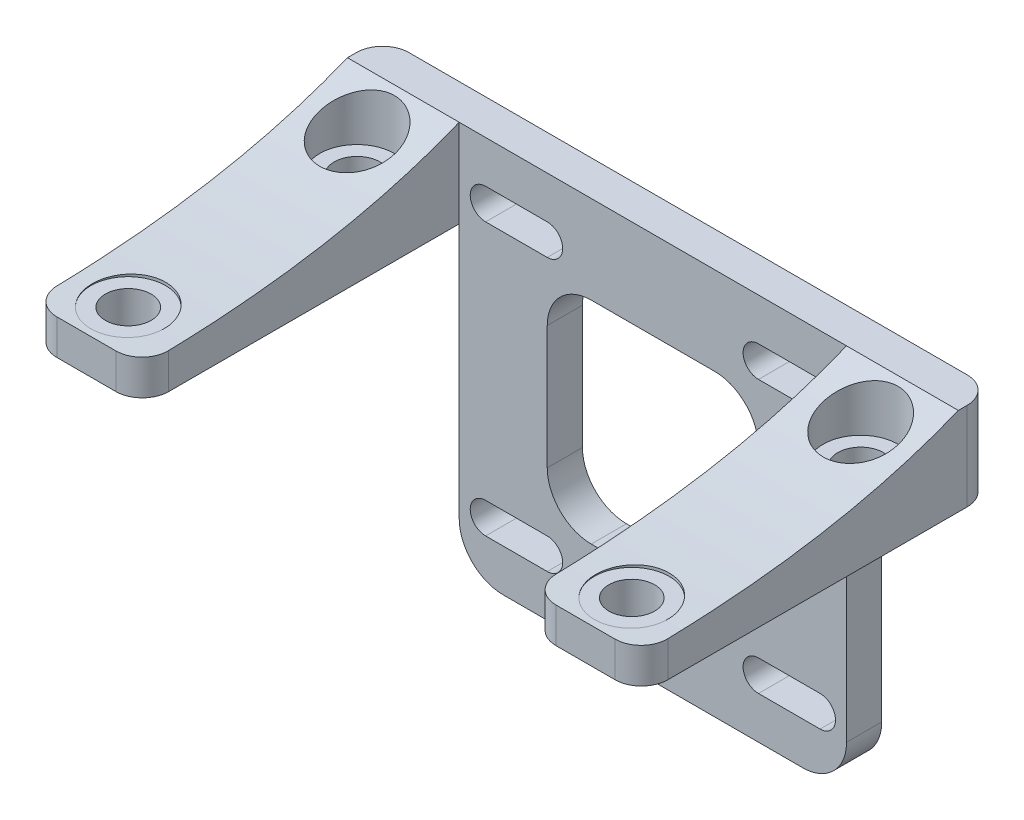
SolidWorks part; units mm, degrees
ref_plane "Front Plane" through (0, 0, 0) normal (0, 0, 1) x (1, 0, 0)
ref_plane "Top Plane" through (0, 0, 0) normal (0, 1, 0) x (1, 0, 0)
ref_plane "Right Plane" through (0, 0, 0) normal (1, 0, 0) x (0, 0, -1)
sketch "Sketch1" plane through (0, 0, 0) normal (0, 0, 1) x (1, 0, 0)
  line L0 (-19, 15.45) -> (-10.25, 15.45) construction
  line L1 (-22, 22) -> (22, 22)
  line L2 (-22, 22) -> (-22, -22)
  line L3 (-22, -22) -> (22, -22)
  line L4 (22, 22) -> (22, -22)
  line L5 (-22, 22) -> (22, -22) construction
  line L6 (-22, -22) -> (22, 22) construction
  line L7 (7, 12) -> (-7, 12)
  line L8 (12, 7) -> (12, -7)
  line L9 (7, -12) -> (-7, -12)
  line L10 (-12, 7) -> (-12, -7)
  line L11 (12, 12) -> (-12, -12) construction
  line L12 (12, -12) -> (-12, 12) construction
  line L13 (-19, 17.2) -> (-12, 17.2)
  line L14 (-19, 13.7) -> (-12, 13.7)
  line L15 (0, 0) -> (50000, 0) construction
  line L16 (-19, -17.2) -> (-12, -17.2)
  line L19 (12, 17.2) -> (19, 17.2)
  line L20 (12, 13.7) -> (19, 13.7)
  line L21 (10.25, 15.45) -> (19, 15.45) construction
  line L22 (-19, -13.7) -> (-12, -13.7)
  line L23 (12, -13.7) -> (19, -13.7)
  line L24 (12, -17.2) -> (19, -17.2)
  arc A0 (-12, -7) -> (-7, -12) centre (-7, -7) ccw
  arc A1 (7, -12) -> (12, -7) centre (7, -7) ccw
  arc A2 (12, 7) -> (7, 12) centre (7, 7) ccw
  arc A3 (-7, 12) -> (-12, 7) centre (-7, 7) ccw
  arc A4 (-19, 17.2) -> (-19, 13.7) centre (-19, 15.45) ccw
  arc A5 (19, 13.7) -> (19, 17.2) centre (19, 15.45) ccw
  circle A8 centre (0, 0) radius 12 construction
  arc A9 (12, 17.2) -> (12, 13.7) centre (12, 15.45) ccw
  arc A10 (-12, 17.2) -> (-12, 13.7) centre (-12, 15.45) cw
  arc A11 (-19, -17.2) -> (-19, -13.7) centre (-19, -15.45) cw
  arc A12 (-12, -17.2) -> (-12, -13.7) centre (-12, -15.45) ccw
  arc A13 (12, -17.2) -> (12, -13.7) centre (12, -15.45) cw
  arc A14 (19, -13.7) -> (19, -17.2) centre (19, -15.45) cw
  point P0 (0, 0)
  point P6 (0, 0)
  dimension "D4" = 5
  dimension "D9" = 1.75
  dimension "D1" = 44
  dimension "D2" = 44
  dimension "D3" = 24
  dimension "D5" = 38
  dimension "D6" = 1.75
  dimension "D7" = 15.45
  dimension "D8" = 7
extrude "Boss-Extrude1" add sketch "Sketch1" along normal blind 4
sketch "Sketch2" plane through (22, 0, 0) normal (1, 0, 0) x (0, 0, -1)
  line L0 (0, 12) -> (-40, 12)
  line L1 (0, -22) -> (0, 22) construction
  line L2 (0, 12) -> (0, 22)
  line L3 (0, 22) -> (-4, 22)
  line L4 (-40, 12) -> (-40, 16)
  line L5 (-40, 16) -> (0, 16) construction
  spline S0 degree 2 poles (-40, 16) (-18.3297, 16.1194) (-4, 22) knots 0 0 0 1 1 1
  dimension "D1" = 4
  dimension "D2" = 40
  dimension "D3" = 12
extrude "Boss-Extrude2" add sketch "Sketch2" along normal blind 12.7
sketch "Sketch3" plane through (0, 12, 0) normal (0, -1, 0) x (1, 0, 0)
  line L0 (34.7, 0) -> (22, 0) construction
  line L1 (34.7, 40) -> (34.7, 0) construction
  line L2 (34.7, 40) -> (22, 40) construction
  circle A0 centre (28.6, 35) radius 2.6
  circle A1 centre (28.6, 9) radius 2.6
  dimension "D2" = 5.2
  dimension "D1" = 6.1
  dimension "D3" = 5
  dimension "D4" = 9
extrude "Cut-Extrude1" cut sketch "Sketch3" against normal through all
ref_plane "Plane1" through (0, 16, 0) normal (0, -1, 0) x (-1, 0, 0)
sketch "Sketch4" plane through (0, 16, 0) normal (0, -1, 0) x (-1, 0, 0)
  circle A0 centre (-28.6, -9) radius 4.25
  circle A1 centre (-28.6, -35) radius 4.25
  dimension "D1" = 8.5
  dimension "D2" = 8.5
extrude "Cut-Extrude2" cut sketch "Sketch4" against normal through all
ref_plane "Plane2" through (0, 0, 0) normal (1, 0, 0) x (0, 0, -1)
mirror "Mirror1" about plane through (0, 0, 0) normal (1, 0, 0) of "Cut-Extrude1", "Cut-Extrude2", "Boss-Extrude2"
fillet "Fillet1" radius 3 6 edges at (34.7, 17, 0) (-34.7, 17, 0) (34.7, 14, 40) (22, 14, 40) (-22, 14, 40) (-34.7, 14, 40)
fillet "Fillet2" radius 5 2 edges at (22, -22, 2) (-22, -22, 2)
